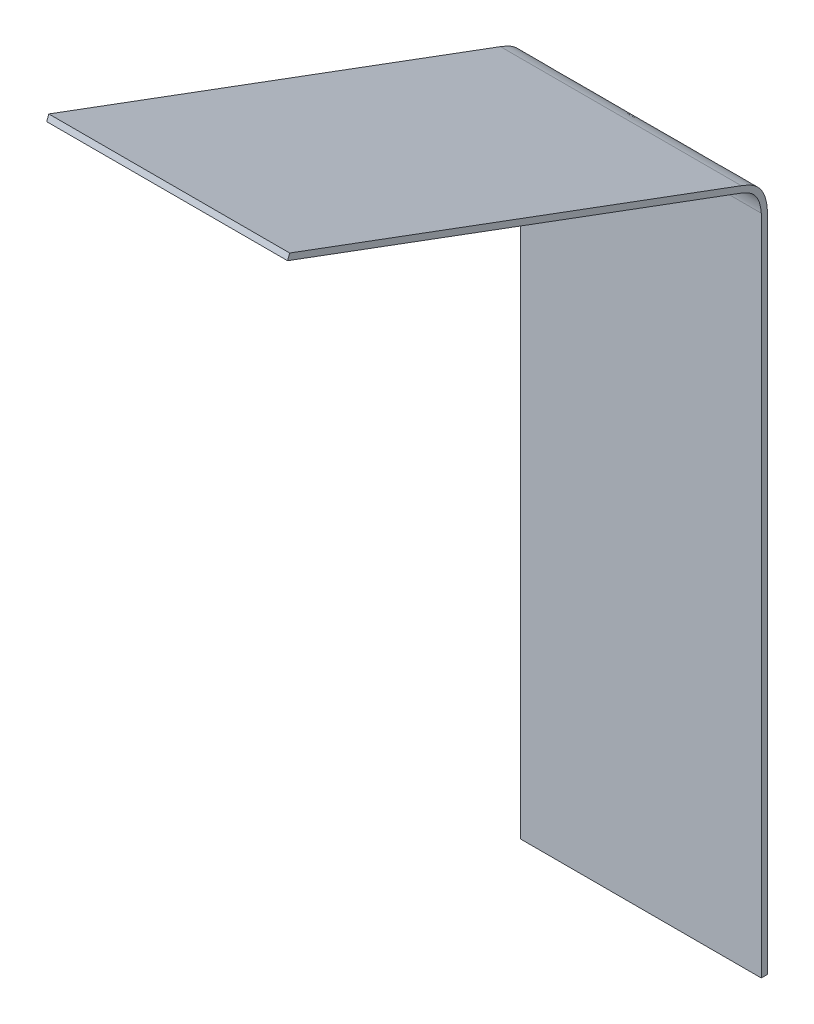
SolidWorks part; units mm, degrees
ref_plane "前视基准面" through (0, 0, 0) normal (0, 0, 1) x (1, 0, 0)
ref_plane "上视基准面" through (0, 0, 0) normal (0, 1, 0) x (1, 0, 0)
ref_plane "右视基准面" through (0, 0, 0) normal (1, 0, 0) x (0, 0, -1)
sketch "草图1" plane through (0, 0, 0) normal (0, 0, 1) x (1, 0, 0)
  line L1 (-10, -27.5) -> (10, -27.5)
  line L2 (-10, -27.5) -> (-10, 27.5)
  line L3 (-10, 27.5) -> (10, 27.5)
  line L4 (10, -27.5) -> (10, 27.5)
  line L5 (-10, -27.5) -> (10, 27.5) construction
  line L6 (-10, 27.5) -> (10, -27.5) construction
  point P0 (0, 0)
  dimension "D1" = 55
  dimension "D2" = 20
extrude "凸台-拉伸1" add sketch "草图1" along normal blind 0.5
sketch "草图2" plane through (-10, 0, 0) normal (-1, 0, 0) x (0, 0, 1)
  line L0 (0.5, 27.5) -> (0.5, -27.5) construction
  line L1 (2.1563, 30.3054) -> (39.6598, 44.2154)
  line L2 (2.3301, 29.8366) -> (39.8336, 43.7466)
  line L3 (39.6598, 44.2154) -> (39.8336, 43.7466)
  line L4 (0, 27.5) -> (0.5, 27.5)
  spline S0 degree 3 poles (0.5, 27.5) (0.5, 27.6558) (0.711, 29.0473) (1.4936, 29.5263) (2.3301, 29.8366) knots 0 0 0 0 0.267128 1 1 1 1
  spline S1 degree 1 poles (0, 27.5) (2.1563, 30.3054) knots 0 0 1 1 construction
  spline S2 degree 3 poles (0, 27.5) (0, 27.6387) (0.0317, 27.8865) (0.1423, 28.4225) (0.3318, 28.9128) (0.6858, 29.4644) (1.2859, 29.9522) (1.8653, 30.1975) (2.1563, 30.3054) knots 0 0 0 0 0.125 0.25 0.375 0.5 0.75 1 1 1 1
  point P6 (2.0631, 29.8077)
  point P11 (0.6535, 28.3341)
  point P13 (1.2808, 29.2847)
  point P14 (1.0953, 29.1132)
  dimension "D2" = 40
  dimension "D3" = 40
  dimension "D1" = 0.5
extrude "凸台-拉伸2" add sketch "草图2" against normal up to surface (20 mm away) up to face at (10, 0, 0.25)
